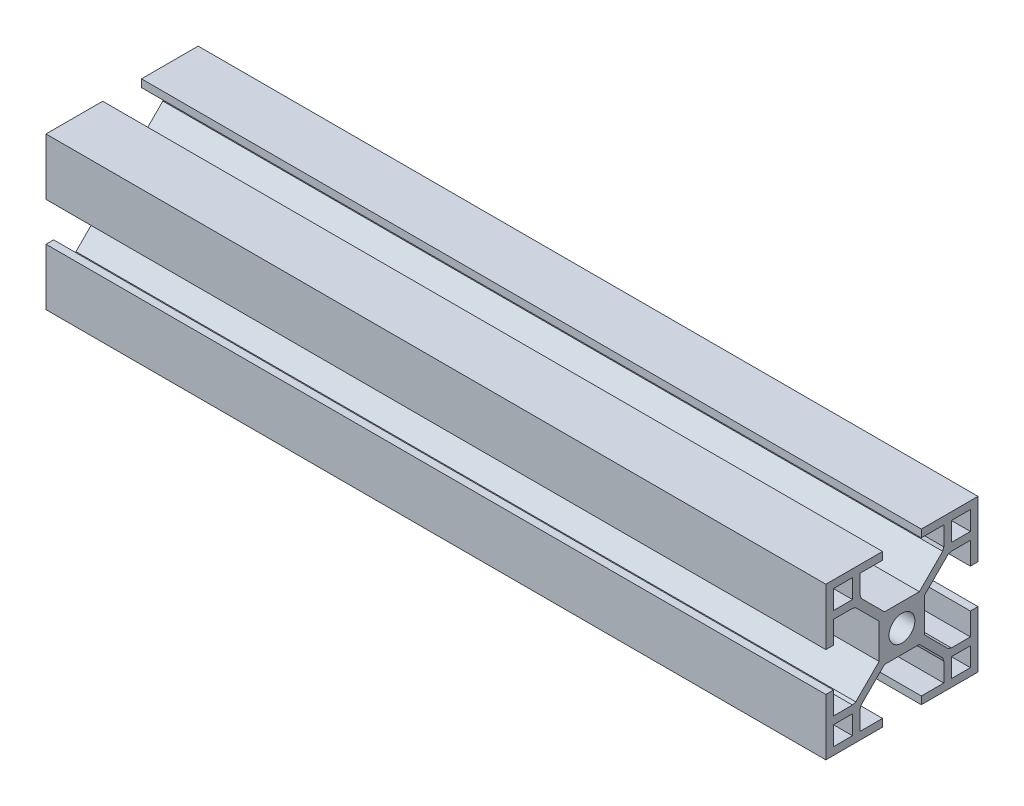
SolidWorks part; units mm, degrees
ref_plane "前视基准面" through (0, 0, 0) normal (0, 0, 1) x (1, 0, 0)
ref_plane "上视基准面" through (0, 0, 0) normal (0, 1, 0) x (1, 0, 0)
ref_plane "右视基准面" through (0, 0, 0) normal (1, 0, 0) x (0, 0, -1)
sketch "草图1" plane through (0, 0, 0) normal (1, 0, 0) x (0, 0, -1)
  line L0 (0, 0) -> (0, 6) construction
  line L5 (0, 6) -> (4.5858, 6)
  line L6 (6, 0) -> (6, -4.5858)
  line L10 (12.133, -10.7188) -> (6, -4.5858)
  line L11 (10.7188, 12.133) -> (4.5858, 6)
  line L12 (20, 20) -> (20, 5.1)
  line L18 (20, -20) -> (5.1, -20)
  line L22 (12.133, -10.7188) -> (13, -11)
  line L23 (18, -13) -> (18, -18)
  line L24 (18, -15.5) -> (18, -13)
  line L28 (18, -13) -> (13, -13)
  line L32 (13, -13) -> (13, -18)
  line L33 (18, -18) -> (13, -18)
  line L34 (11, -13) -> (11, -18)
  line L38 (11, -18) -> (5.1, -18)
  line L42 (10.7188, -12.133) -> (11, -13)
  line L43 (10.7188, -12.133) -> (4.5858, -6)
  line L44 (4.5858, -6) -> (0, -6)
  line L45 (10.7188, 12.133) -> (11, 13)
  line L46 (5.1, -18) -> (5.1, -20)
  line L47 (13, 18) -> (18, 18)
  line L49 (15.5, 18) -> (13, 18)
  line L56 (13, 18) -> (13, 13)
  line L59 (13, 13) -> (18, 13)
  line L60 (18, 18) -> (18, 13)
  line L61 (13, 11) -> (18, 11)
  line L62 (18, 11) -> (18, 5.1)
  line L63 (12.133, 10.7188) -> (13, 11)
  line L64 (12.133, 10.7188) -> (6, 4.5858)
  line L65 (6, 4.5858) -> (6, 0)
  line L66 (18, 5.1) -> (20, 5.1)
  line L67 (11, 18) -> (5.1, 18)
  line L68 (11, 13) -> (11, 18)
  line L69 (5.1, 18) -> (5.1, 20)
  line L70 (20, 20) -> (5.1, 20)
  line L71 (18, -11) -> (18, -5.1)
  line L72 (13, -11) -> (18, -11)
  line L73 (18, -5.1) -> (20, -5.1)
  line L74 (20, -20) -> (20, -5.1)
  line L75 (0, 0) -> (6, 0) construction
  line L76 (0, -6) -> (-4.5858, -6)
  line L77 (-10.7188, -12.133) -> (-4.5858, -6)
  line L78 (-20, -20) -> (-20, -5.1)
  line L79 (-10.7188, -12.133) -> (-11, -13)
  line L80 (-13, -18) -> (-18, -18)
  line L81 (-15.5, -18) -> (-13, -18)
  line L82 (-13, -18) -> (-13, -13)
  line L83 (-13, -13) -> (-18, -13)
  line L84 (-18, -18) -> (-18, -13)
  line L85 (-13, -11) -> (-18, -11)
  line L86 (-18, -11) -> (-18, -5.1)
  line L87 (-12.133, -10.7188) -> (-13, -11)
  line L88 (-12.133, -10.7188) -> (-6, -4.5858)
  line L89 (-6, -4.5858) -> (-6, 0)
  line L90 (-18, -5.1) -> (-20, -5.1)
  line L91 (-11, -18) -> (-5.1, -18)
  line L92 (-11, -13) -> (-11, -18)
  line L93 (-5.1, -18) -> (-5.1, -20)
  line L94 (-20, -20) -> (-5.1, -20)
  line L95 (0, 0) -> (0, -6) construction
  line L96 (-6, 0) -> (-6, 4.5858)
  line L97 (-12.133, 10.7188) -> (-6, 4.5858)
  line L98 (-20, 20) -> (-5.1, 20)
  line L99 (-12.133, 10.7188) -> (-13, 11)
  line L100 (-18, 13) -> (-18, 18)
  line L101 (-18, 15.5) -> (-18, 13)
  line L102 (-18, 13) -> (-13, 13)
  line L103 (-13, 13) -> (-13, 18)
  line L104 (-18, 18) -> (-13, 18)
  line L105 (-11, 13) -> (-11, 18)
  line L106 (-11, 18) -> (-5.1, 18)
  line L107 (-10.7188, 12.133) -> (-11, 13)
  line L108 (-10.7188, 12.133) -> (-4.5858, 6)
  line L109 (-4.5858, 6) -> (0, 6)
  line L110 (-5.1, 18) -> (-5.1, 20)
  line L111 (-18, 11) -> (-18, 5.1)
  line L112 (-13, 11) -> (-18, 11)
  line L113 (-18, 5.1) -> (-20, 5.1)
  line L114 (-20, 20) -> (-20, 5.1)
  line L115 (0, 0) -> (-6, 0) construction
  circle A0 centre (0, 0) radius 3.4
extrude "凸台-拉伸1" add sketch "草图1" along normal blind 205 contours L84 L80 L82 L83 | L33 L23 L28 L32 | L60 L47 L56 L59 | L12 L66 L62 L61 L63 L64 L65 L6 L10 L22 L72 L71 L73 L74 L18 L46 L38 L34 L42 L43 L44 L76 L77 L79 L92 L91 L93 L94 L78 L90 L86 L85 L87 L88 L89 L96 L97 L99 L112 L111 L113 L114 L98 L110 L106 L105 L107 L108 L109 L5 L11 L45 L68 L67 L69 L70 | A0 | L102 L103 L104 L100
